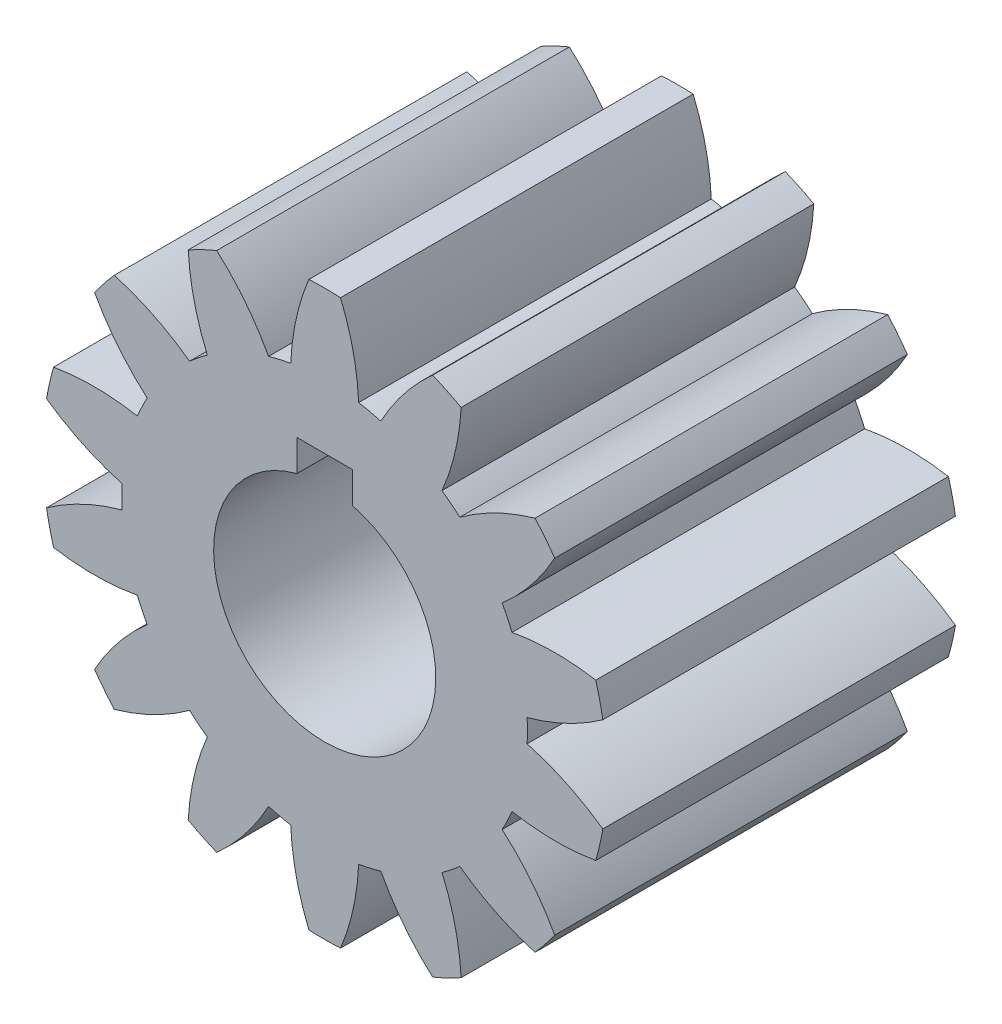
SolidWorks part; units mm, degrees
material "AISI 4130 Steel, annealed at 865C"
ref_plane "Front Plane" through (0, 0, 0) normal (0, 0, 1) x (1, 0, 0)
ref_plane "Top Plane" through (0, 0, 0) normal (0, 1, 0) x (1, 0, 0)
ref_plane "Right Plane" through (0, 0, 0) normal (1, 0, 0) x (0, 0, -1)
ref_plane "Plane1" through (0, 0, 12.7) normal (0, 0, 1) x (1, 0, 0)
sketch "Sketch1" plane through (0, 0, 12.7) normal (0, 0, 1) x (1, 0, 0)
  line L0 (-1, 3.873) -> (-1, 5)
  line L1 (-1, 5) -> (1, 5)
  line L2 (1, 5) -> (1, 3.873)
  arc A0 (-4.9146, 8.8923) -> (-4.2257, 5.9556) centre (3.6995, 9.3637) ccw
  arc A1 (-4.2257, 5.9556) -> (-4.866, 5.4451) centre (0, 0) ccw
  arc A2 (-4.866, 5.4451) -> (-7.5757, 6.7701) centre (-9.9522, -1.5231) ccw
  arc A3 (-7.5757, 6.7701) -> (-8.2861, 5.8793) centre (0, 0) ccw
  arc A4 (-8.2861, 5.8793) -> (-6.3913, 3.5324) centre (-0.7297, 10.0416) ccw
  arc A5 (-6.3913, 3.5324) -> (-6.7466, 2.7945) centre (0, 0) ccw
  arc A6 (-6.7466, 2.7945) -> (-9.7629, 2.8126) centre (-8.3058, -5.6903) ccw
  arc A7 (-9.7629, 2.8126) -> (-10.0164, 1.7019) centre (0, 0) ccw
  arc A8 (-10.0164, 1.7019) -> (-7.291, 0.4095) centre (-5.0143, 8.7306) ccw
  arc A9 (-7.291, 0.4095) -> (-7.291, -0.4095) centre (0, 0) ccw
  arc A10 (-7.291, -0.4095) -> (-10.0164, -1.7019) centre (-5.0143, -8.7306) ccw
  arc A11 (-10.0164, -1.7019) -> (-9.7629, -2.8126) centre (0, 0) ccw
  arc A12 (-9.7629, -2.8126) -> (-6.7466, -2.7945) centre (-8.3058, 5.6903) ccw
  arc A13 (-6.7466, -2.7945) -> (-6.3913, -3.5324) centre (0, 0) ccw
  arc A14 (-6.3913, -3.5324) -> (-8.2861, -5.8793) centre (-0.7297, -10.0416) ccw
  arc A15 (-8.2861, -5.8793) -> (-7.5757, -6.7701) centre (0, 0) ccw
  arc A16 (-7.5757, -6.7701) -> (-4.866, -5.4451) centre (-9.9522, 1.5231) ccw
  arc A17 (-4.866, -5.4451) -> (-4.2257, -5.9556) centre (0, 0) ccw
  arc A18 (-4.2257, -5.9556) -> (-4.9146, -8.8923) centre (3.6995, -9.3637) ccw
  arc A19 (-4.9146, -8.8923) -> (-3.8881, -9.3866) centre (0, 0) ccw
  arc A20 (-3.8881, -9.3866) -> (-2.0216, -7.0171) centre (-9.6274, -2.9458) ccw
  arc A21 (-2.0216, -7.0171) -> (-1.2232, -7.1993) centre (0, 0) ccw
  arc A22 (-1.2232, -7.1993) -> (-0.5697, -10.144) centre (7.3959, -6.8313) ccw
  arc A23 (-0.5697, -10.144) -> (0.5697, -10.144) centre (0, 0) ccw
  arc A24 (0.5697, -10.144) -> (1.2232, -7.1993) centre (-7.3959, -6.8313) ccw
  arc A25 (1.2232, -7.1993) -> (2.0216, -7.0171) centre (0, 0) ccw
  arc A26 (2.0216, -7.0171) -> (3.8881, -9.3866) centre (9.6274, -2.9458) ccw
  arc A27 (3.8881, -9.3866) -> (4.9146, -8.8923) centre (0, 0) ccw
  arc A28 (4.9146, -8.8923) -> (4.2257, -5.9556) centre (-3.6995, -9.3637) ccw
  arc A29 (4.2257, -5.9556) -> (4.866, -5.4451) centre (0, 0) ccw
  arc A30 (4.866, -5.4451) -> (7.5757, -6.7701) centre (9.9522, 1.5231) ccw
  arc A31 (7.5757, -6.7701) -> (8.2861, -5.8793) centre (0, 0) ccw
  arc A32 (8.2861, -5.8793) -> (6.3913, -3.5324) centre (0.7297, -10.0416) ccw
  arc A33 (6.3913, -3.5324) -> (6.7466, -2.7945) centre (0, 0) ccw
  arc A34 (6.7466, -2.7945) -> (9.7629, -2.8126) centre (8.3058, 5.6903) ccw
  arc A35 (9.7629, -2.8126) -> (10.0164, -1.7019) centre (0, 0) ccw
  arc A36 (10.0164, -1.7019) -> (7.291, -0.4095) centre (5.0143, -8.7306) ccw
  arc A37 (7.291, -0.4095) -> (7.291, 0.4095) centre (0, 0) ccw
  arc A38 (7.291, 0.4095) -> (10.0164, 1.7019) centre (5.0143, 8.7306) ccw
  arc A39 (10.0164, 1.7019) -> (9.7629, 2.8126) centre (0, 0) ccw
  arc A40 (9.7629, 2.8126) -> (6.7466, 2.7945) centre (8.3058, -5.6903) ccw
  arc A41 (6.7466, 2.7945) -> (6.3913, 3.5324) centre (0, 0) ccw
  arc A42 (6.3913, 3.5324) -> (8.2861, 5.8793) centre (0.7297, 10.0416) ccw
  arc A43 (8.2861, 5.8793) -> (7.5757, 6.7701) centre (0, 0) ccw
  arc A44 (7.5757, 6.7701) -> (4.866, 5.4451) centre (9.9522, -1.5231) ccw
  arc A45 (4.866, 5.4451) -> (4.2257, 5.9556) centre (0, 0) ccw
  arc A46 (4.2257, 5.9556) -> (4.9146, 8.8923) centre (-3.6995, 9.3637) ccw
  arc A47 (4.9146, 8.8923) -> (3.8881, 9.3866) centre (0, 0) ccw
  arc A48 (3.8881, 9.3866) -> (2.0216, 7.0171) centre (9.6274, 2.9458) ccw
  arc A49 (2.0216, 7.0171) -> (1.2232, 7.1993) centre (0, 0) ccw
  arc A50 (1.2232, 7.1993) -> (0.5697, 10.144) centre (-7.3959, 6.8313) ccw
  arc A51 (0.5697, 10.144) -> (-0.5697, 10.144) centre (0, 0) ccw
  arc A52 (-0.5697, 10.144) -> (-1.2232, 7.1993) centre (7.3959, 6.8313) ccw
  arc A53 (-1.2232, 7.1993) -> (-2.0216, 7.0171) centre (0, 0) ccw
  arc A54 (-2.0216, 7.0171) -> (-3.8881, 9.3866) centre (-9.6274, 2.9458) ccw
  arc A55 (-3.8881, 9.3866) -> (-4.9146, 8.8923) centre (0, 0) ccw
  arc A56 (1, 3.873) -> (-1, 3.873) centre (0, 0) cw
extrude "Boss-Extrude1" add sketch "Sketch1" against normal blind 12.7
